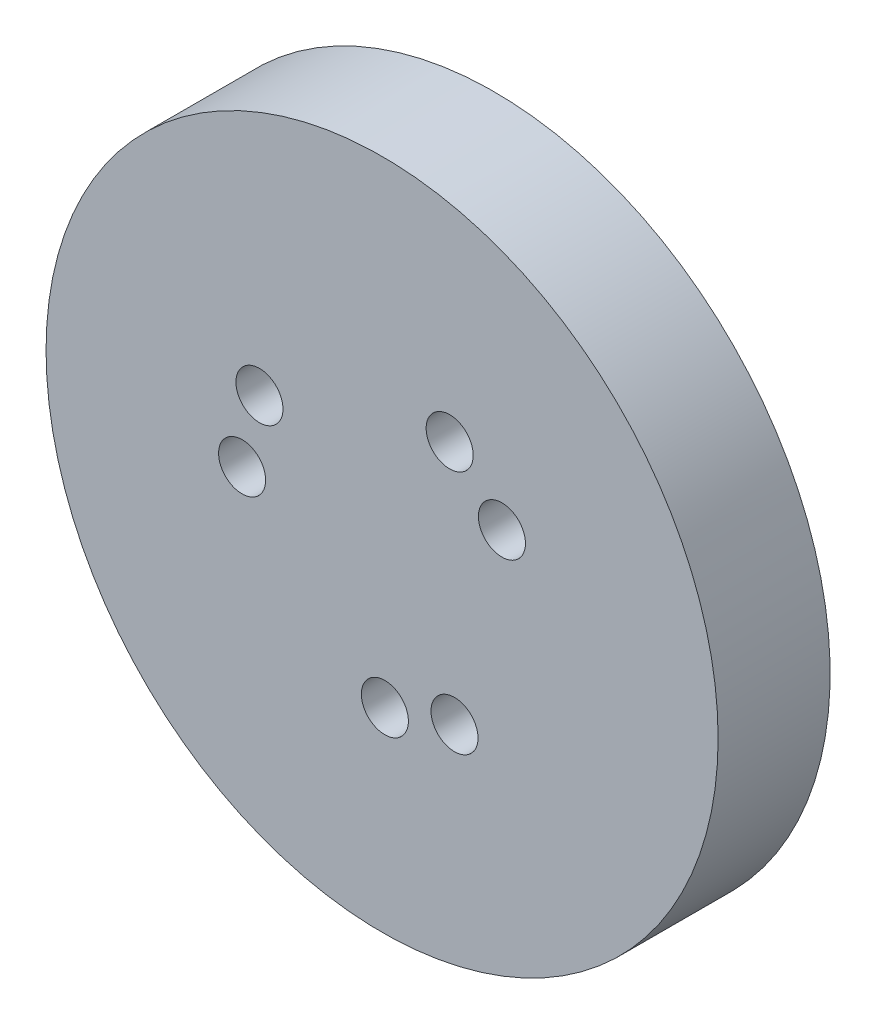
SolidWorks part; units mm, degrees
ref_plane "정면" through (0, 0, 0) normal (0, 0, 1) x (1, 0, 0)
ref_plane "윗면" through (0, 0, 0) normal (0, 1, 0) x (1, 0, 0)
ref_plane "우측면" through (0, 0, 0) normal (1, 0, 0) x (0, 0, -1)
sketch "스케치2" plane through (0, 0, 0) normal (0, 0, 1) x (1, 0, 0)
  circle A0 centre (0, 0) radius 15
  circle A1 centre (0, 0) radius 10
  point P13 (4.2374, 0.9394)
  dimension "D1" = 30
  dimension "D2" = 20
extrude "보스-돌출2" add sketch "스케치2" along normal blind 4.6
sketch "스케치23" plane through (0, 0, 4.6) normal (0, 0, 1) x (1, 0, 0)
  line L0 (0, 0) -> (10.6986, 6.4645) construction
  line L1 (0, 0) -> (6.033, 10.9477) construction
  line L2 (0, 0) -> (15, 0) construction
  circle A0 centre (10.6986, 6.4645) radius 2.1
  circle A1 centre (0, 0) radius 15 construction
  circle A2 centre (6.033, 10.9477) radius 2.1
  circle A3 centre (6.4645, -10.6986) radius 2.1
  circle A4 centre (0.2491, -12.4975) radius 2.1
  circle A5 centre (-12.4975, -0.2491) radius 2.1
  circle A6 centre (-10.9477, 6.033) radius 2.1
  point P21 (0, 0)
  dimension "D1" = 4.2
  dimension "D3" = 30
  dimension "D4" = 3
  dimension "D2" = 12.5
extrude "컷-돌출8" cut sketch "스케치23" against normal offset from surface 1.5 and the other way blind 20 up to face at (15, 0, 0)
sketch "스케치26" plane through (0, 0, 1.5) normal (0, 0, 1) x (1, 0, 0)
  circle A0 centre (6.033, 10.9477) radius 1.2
  circle A1 centre (10.6986, 6.4645) radius 1.2
  circle A2 centre (6.4645, -10.6986) radius 1.2
  circle A3 centre (0.2491, -12.4975) radius 1.2
  circle A4 centre (-10.9477, 6.033) radius 1.2
  circle A5 centre (-12.4975, -0.2491) radius 1.2
extrude "컷-돌출9" cut sketch "스케치26" against normal blind 10
sketch "스케치3" plane through (0, 0, 4.6) normal (0, 0, 1) x (1, 0, 0)
  circle A0 centre (0, 0) radius 10
  dimension "D1" = 20
curve "나선형 곡선1"
sketch "스케치4" plane through (0, 0, 4.6) normal (0, 0, 1) x (1, 0, 0)
  circle A0 centre (0, 0) radius 10
  dimension "D1" = 20
curve "나선형 곡선2"
sketch "스케치5" plane through (0, 0, 4.6) normal (0, 0, 1) x (1, 0, 0)
  circle A0 centre (0, 0) radius 10
  dimension "D1" = 20
curve "나선형 곡선3"
sketch "스케치6" plane through (0, 0, 4.6) normal (0, 0, 1) x (1, 0, 0)
  circle A0 centre (0, 0) radius 10
  dimension "D1" = 20
curve "나선형 곡선4"
sketch "스케치8" plane through (0, 0, 4.6) normal (0, 0, 1) x (1, 0, 0)
  arc A0 (-2.125, 3.6806) -> (-3.9937, -1.4536) centre (0, 0) ccw
  arc A1 (2.125, -3.6806) -> (3.9937, 1.4536) centre (0, 0) ccw
  arc A2 (-9.3969, -3.4202) -> (5, -8.6603) centre (0, 0) ccw
  arc A3 (9.3969, 3.4202) -> (-5, 8.6603) centre (0, 0) ccw
  spline S0 degree 3 poles (-1935.5381, 448.3535) (81.1193, 182.5863) (35.7886, -8.3056) (-0.0084, -9.6041) (-1.2597, -9.3952) (-3.5447, -8.5348) (-4.5777, -7.8842) (-6.2849, -6.2722) (-6.9587, -5.3118) (-7.872, -3.2507) (-8.1116, -2.151) (-8.1543, 0.0095) (-7.9579, 1.0694) (-7.195, 2.9909) (-6.6292, 3.8519) (-5.2463, 5.2605) (-4.4301, 5.8078) (-2.6949, 6.533) (-1.7768, 6.7109) (0.0106, 6.7046) (0.8791, 6.5207) (2.4371, 5.8552) (3.1261, 5.3742) (4.2361, 4.2204) (4.657, 3.5484) (5.194, 2.1391) (5.3103, 1.4026) (5.2548, -0.0117) (5.0835, -0.6888) (4.5154, -1.8832) (4.1192, -2.4003) (-12.3561, -16.8592) (-106.9283, 102.6405) (1865.2864, 715.7147) knots -1.641124 -1.641124 -1.641124 -1.641124 0.0625 0.0625 0.125 0.125 0.1875 0.1875 0.25 0.25 0.3125 0.3125 0.375 0.375 0.4375 0.4375 0.5 0.5 0.5625 0.5625 0.625 0.625 0.6875 0.6875 0.75 0.75 0.8125 0.8125 0.875 0.875 0.9375 0.9375 3.102152 3.102152 3.102152 3.102152 only from (5, -8.6603) to (2.125, -3.6806) construction
  spline S1 degree 3 poles (777.6447, 1828.2772) (165.7262, -111.5927) (-14.3941, -33.8027) (-9.4567, 1.676) (-9.0337, 2.872) (-7.7897, 4.9729) (-6.9695, 5.8772) (-5.0856, 7.2786) (-4.0228, 7.7753) (-1.8343, 8.3169) (-0.7097, 8.3618) (1.4254, 8.0288) (2.435, 7.6513) (4.1948, 6.5664) (4.9445, 5.8596) (6.0916, 4.2531) (6.4889, 3.3543) (6.9017, 1.5195) (6.9175, 0.5844) (6.6009, -1.1747) (6.269, -1.998) (5.3431, -3.4168) (4.7497, -4.0118) (3.4207, -4.9047) (2.6858, -5.2024) (1.2047, -5.4866) (0.4592, -5.4732) (-0.924, -5.173) (-1.561, -4.8867) (-2.6387, -4.1198) (-3.0791, -3.6398) (-14.4575, 15.096) (119.6491, 87.4805) (380.9378, -1961.2311) knots -1.641124 -1.641124 -1.641124 -1.641124 0.0625 0.0625 0.125 0.125 0.1875 0.1875 0.25 0.25 0.3125 0.3125 0.375 0.375 0.4375 0.4375 0.5 0.5 0.5625 0.5625 0.625 0.625 0.6875 0.6875 0.75 0.75 0.8125 0.8125 0.875 0.875 0.9375 0.9375 3.102152 3.102152 3.102152 3.102152 only from (-9.3969, -3.4202) to (-3.9937, -1.4536) construction
  spline S2 degree 3 poles (-777.6447, -1828.2772) (-165.7262, 111.5927) (14.3941, 33.8027) (9.4567, -1.676) (9.0337, -2.872) (7.7897, -4.9729) (6.9695, -5.8772) (5.0856, -7.2786) (4.0228, -7.7753) (1.8343, -8.3169) (0.7097, -8.3618) (-1.4254, -8.0288) (-2.435, -7.6513) (-4.1948, -6.5664) (-4.9445, -5.8596) (-6.0916, -4.2531) (-6.4889, -3.3543) (-6.9017, -1.5195) (-6.9175, -0.5844) (-6.6009, 1.1747) (-6.269, 1.998) (-5.3431, 3.4168) (-4.7497, 4.0118) (-3.4207, 4.9047) (-2.6858, 5.2024) (-1.2047, 5.4866) (-0.4592, 5.4732) (0.924, 5.173) (1.561, 4.8867) (2.6387, 4.1198) (3.0791, 3.6398) (14.4575, -15.096) (-119.6491, -87.4805) (-380.9378, 1961.2311) knots -1.641124 -1.641124 -1.641124 -1.641124 0.0625 0.0625 0.125 0.125 0.1875 0.1875 0.25 0.25 0.3125 0.3125 0.375 0.375 0.4375 0.4375 0.5 0.5 0.5625 0.5625 0.625 0.625 0.6875 0.6875 0.75 0.75 0.8125 0.8125 0.875 0.875 0.9375 0.9375 3.102152 3.102152 3.102152 3.102152 only from (9.3969, 3.4202) to (3.9937, 1.4536) construction
  spline S3 degree 3 poles (1935.5381, -448.3535) (-81.1193, -182.5863) (-35.7886, 8.3056) (0.0084, 9.6041) (1.2597, 9.3952) (3.5447, 8.5348) (4.5777, 7.8842) (6.2849, 6.2722) (6.9587, 5.3118) (7.872, 3.2507) (8.1116, 2.151) (8.1543, -0.0095) (7.9579, -1.0694) (7.195, -2.9909) (6.6292, -3.8519) (5.2463, -5.2605) (4.4301, -5.8078) (2.6949, -6.533) (1.7768, -6.7109) (-0.0106, -6.7046) (-0.8791, -6.5207) (-2.4371, -5.8552) (-3.1261, -5.3742) (-4.2361, -4.2204) (-4.657, -3.5484) (-5.194, -2.1391) (-5.3103, -1.4026) (-5.2548, 0.0117) (-5.0835, 0.6888) (-4.5154, 1.8832) (-4.1192, 2.4003) (12.3561, 16.8592) (106.9283, -102.6405) (-1865.2864, -715.7147) knots -1.641124 -1.641124 -1.641124 -1.641124 0.0625 0.0625 0.125 0.125 0.1875 0.1875 0.25 0.25 0.3125 0.3125 0.375 0.375 0.4375 0.4375 0.5 0.5 0.5625 0.5625 0.625 0.625 0.6875 0.6875 0.75 0.75 0.8125 0.8125 0.875 0.875 0.9375 0.9375 3.102152 3.102152 3.102152 3.102152 only from (-5, 8.6603) to (-2.125, 3.6806) construction
  spline S4 degree 3 poles (5, -8.6603) (3.8065, -9.211) (2.5251, -9.5122) (-0.0084, -9.6041) (-1.2597, -9.3952) (-3.5447, -8.5348) (-4.5777, -7.8842) (-6.2849, -6.2722) (-6.9587, -5.3118) (-7.872, -3.2507) (-8.1116, -2.151) (-8.1543, 0.0095) (-7.9579, 1.0694) (-7.195, 2.9909) (-6.6292, 3.8519) (-5.2463, 5.2605) (-4.4301, 5.8078) (-2.6949, 6.533) (-1.7768, 6.7109) (0.0106, 6.7046) (0.8791, 6.5207) (2.4371, 5.8552) (3.1261, 5.3742) (4.2361, 4.2204) (4.657, 3.5484) (5.194, 2.1391) (5.3103, 1.4026) (5.2548, -0.0117) (5.0835, -0.6888) (4.5154, -1.8832) (4.1192, -2.4003) (3.1945, -3.2118) (2.6667, -3.5062) (2.125, -3.6806) knots 0 0 0 0 0.0625 0.0625 0.125 0.125 0.1875 0.1875 0.25 0.25 0.3125 0.3125 0.375 0.375 0.4375 0.4375 0.5 0.5 0.5625 0.5625 0.625 0.625 0.6875 0.6875 0.75 0.75 0.8125 0.8125 0.875 0.875 0.9375 0.9375 1 1 1 1
  spline S5 degree 3 poles (-9.3969, -3.4202) (-9.7321, -2.1492) (-9.8062, -0.835) (-9.4567, 1.676) (-9.0337, 2.872) (-7.7897, 4.9729) (-6.9695, 5.8772) (-5.0856, 7.2786) (-4.0228, 7.7753) (-1.8343, 8.3169) (-0.7097, 8.3618) (1.4254, 8.0288) (2.435, 7.6513) (4.1948, 6.5664) (4.9445, 5.8596) (6.0916, 4.2531) (6.4889, 3.3543) (6.9017, 1.5195) (6.9175, 0.5844) (6.6009, -1.1747) (6.269, -1.998) (5.3431, -3.4168) (4.7497, -4.0118) (3.4207, -4.9047) (2.6858, -5.2024) (1.2047, -5.4866) (0.4592, -5.4732) (-0.924, -5.173) (-1.561, -4.8867) (-2.6387, -4.1198) (-3.0791, -3.6398) (-3.7177, -2.5883) (-3.916, -2.0173) (-3.9937, -1.4536) knots 0 0 0 0 0.0625 0.0625 0.125 0.125 0.1875 0.1875 0.25 0.25 0.3125 0.3125 0.375 0.375 0.4375 0.4375 0.5 0.5 0.5625 0.5625 0.625 0.625 0.6875 0.6875 0.75 0.75 0.8125 0.8125 0.875 0.875 0.9375 0.9375 1 1 1 1
  spline S6 degree 3 poles (9.3969, 3.4202) (9.7321, 2.1492) (9.8062, 0.835) (9.4567, -1.676) (9.0337, -2.872) (7.7897, -4.9729) (6.9695, -5.8772) (5.0856, -7.2786) (4.0228, -7.7753) (1.8343, -8.3169) (0.7097, -8.3618) (-1.4254, -8.0288) (-2.435, -7.6513) (-4.1948, -6.5664) (-4.9445, -5.8596) (-6.0916, -4.2531) (-6.4889, -3.3543) (-6.9017, -1.5195) (-6.9175, -0.5844) (-6.6009, 1.1747) (-6.269, 1.998) (-5.3431, 3.4168) (-4.7497, 4.0118) (-3.4207, 4.9047) (-2.6858, 5.2024) (-1.2047, 5.4866) (-0.4592, 5.4732) (0.924, 5.173) (1.561, 4.8867) (2.6387, 4.1198) (3.0791, 3.6398) (3.7177, 2.5883) (3.916, 2.0173) (3.9937, 1.4536) knots 0 0 0 0 0.0625 0.0625 0.125 0.125 0.1875 0.1875 0.25 0.25 0.3125 0.3125 0.375 0.375 0.4375 0.4375 0.5 0.5 0.5625 0.5625 0.625 0.625 0.6875 0.6875 0.75 0.75 0.8125 0.8125 0.875 0.875 0.9375 0.9375 1 1 1 1
  spline S7 degree 3 poles (-5, 8.6603) (-3.8065, 9.211) (-2.5251, 9.5122) (0.0084, 9.6041) (1.2597, 9.3952) (3.5447, 8.5348) (4.5777, 7.8842) (6.2849, 6.2722) (6.9587, 5.3118) (7.872, 3.2507) (8.1116, 2.151) (8.1543, -0.0095) (7.9579, -1.0694) (7.195, -2.9909) (6.6292, -3.8519) (5.2463, -5.2605) (4.4301, -5.8078) (2.6949, -6.533) (1.7768, -6.7109) (-0.0106, -6.7046) (-0.8791, -6.5207) (-2.4371, -5.8552) (-3.1261, -5.3742) (-4.2361, -4.2204) (-4.657, -3.5484) (-5.194, -2.1391) (-5.3103, -1.4026) (-5.2548, 0.0117) (-5.0835, 0.6888) (-4.5154, 1.8832) (-4.1192, 2.4003) (-3.1945, 3.2118) (-2.6667, 3.5062) (-2.125, 3.6806) knots 0 0 0 0 0.0625 0.0625 0.125 0.125 0.1875 0.1875 0.25 0.25 0.3125 0.3125 0.375 0.375 0.4375 0.4375 0.5 0.5 0.5625 0.5625 0.625 0.625 0.6875 0.6875 0.75 0.75 0.8125 0.8125 0.875 0.875 0.9375 0.9375 1 1 1 1
extrude "보스-돌출3" add sketch "스케치8" against normal blind 4.4
sketch "스케치10" plane through (0, 0, 4.6) normal (0, 0, 1) x (1, 0, 0)
  circle A0 centre (0, 0) radius 4
  dimension "D1" = 8
extrude "보스-돌출4" add sketch "스케치10" along normal blind 0.6
fillet "필렛1" [suppressed] radius 0.1
sketch "스케치25" plane through (0, 0, 5.2) normal (0, 0, 1) x (1, 0, 0)
  circle A0 centre (0, 0) radius 30
extrude "보스-돌출5" add sketch "스케치25" along normal blind 5
sketch "스케치28" plane through (0, 0, 4.6) normal (0, 0, 1) x (1, 0, 0)
  circle A0 centre (10.6986, 6.4645) radius 2.1
  circle A1 centre (6.033, 10.9477) radius 2.1
  circle A2 centre (6.4645, -10.6986) radius 2.1
  circle A3 centre (0.2491, -12.4975) radius 2.1
  circle A4 centre (-12.4975, -0.2491) radius 2.1
  circle A5 centre (-10.9477, 6.033) radius 2.1
extrude "컷-돌출10" cut sketch "스케치28" along normal blind 10
sketch "스케치29" plane through (0, 0, 0) normal (0, 0, -1) x (-1, 0, 0)
  circle A0 centre (0, 0) radius 3.975
  circle A1 centre (0, 0) radius 3.1
extrude "보스-돌출6" add sketch "스케치29" along normal blind 3.4 separate body
sketch "스케치30" plane through (0, 0, 5.2) normal (0, 0, -1) x (-1, 0, 0)
  circle A0 centre (0, 0) radius 30
  circle A1 centre (0, 0) radius 27
extrude "보스-돌출7" add sketch "스케치30" along normal blind 5
